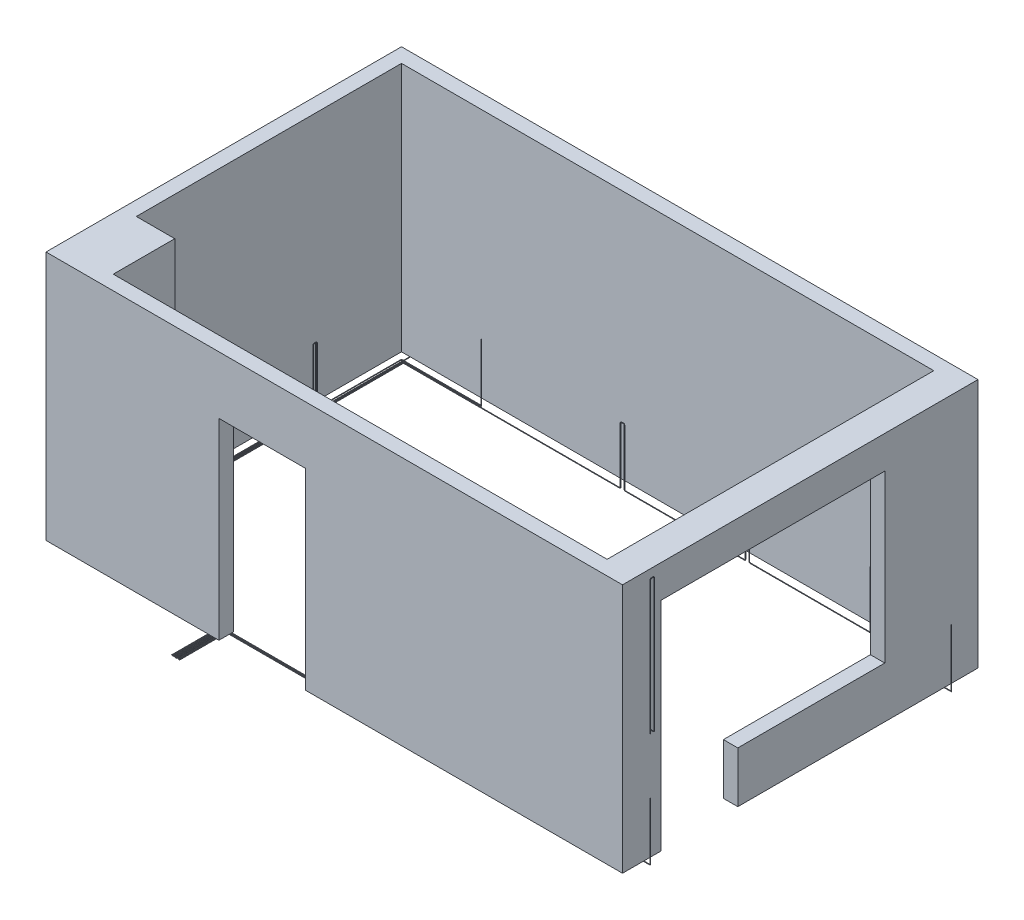
SolidWorks part; units mm, degrees
ref_plane "Front Plane" through (0, 0, 0) normal (0, 0, 1) x (1, 0, 0)
ref_plane "Top Plane" through (0, 0, 0) normal (0, 1, 0) x (1, 0, 0)
ref_plane "Right Plane" through (0, 0, 0) normal (1, 0, 0) x (0, 0, -1)
sketch "LR Dimensions" plane through (0, 0, 0) normal (0, 1, 0) x (1, 0, 0)
  line L0 (-275.7723, 265.5066) -> (-275.7723, -104.4934)
  line L1 (-260.7723, 250.5066) -> (309.2277, 250.5066)
  line L2 (-260.7723, 250.5066) -> (-260.7723, -89.4934)
  line L7 (-275.7723, 265.5066) -> (324.2277, 265.5066)
  line L8 (-260.7723, -89.4934) -> (309.2277, -89.4934) construction
  line L9 (-275.7723, -104.4934) -> (324.2277, -104.4934) construction
  line L10 (-260.7723, -89.4934) -> (-120.7723, -89.4934)
  line L11 (-275.7723, -104.4934) -> (-120.7723, -104.4934)
  line L12 (309.2277, -89.4934) -> (-30.7723, -89.4934)
  line L13 (324.2277, -104.4934) -> (-30.7723, -104.4934)
  line L14 (309.2277, -89.4934) -> (309.2277, -49.4934)
  line L15 (309.2277, 250.5066) -> (309.2277, -89.4934) construction
  line L16 (324.2277, 265.5066) -> (324.2277, -104.4934) construction
  line L17 (324.2277, -104.4934) -> (324.2277, -49.4934)
  line L18 (324.2277, 265.5066) -> (324.2277, 30.5066)
  line L19 (309.2277, 250.5066) -> (309.2277, 30.5066)
  line L20 (309.2277, 30.5066) -> (324.2277, 30.5066)
  line L21 (309.2277, -49.4934) -> (324.2277, -49.4934)
  line L22 (-30.7723, -89.4934) -> (-30.7723, -104.4934)
  line L23 (-120.7723, -104.4934) -> (-120.7723, -89.4934)
  line L24 (-260.7723, -25.4934) -> (-220.7723, -25.4934)
  line L25 (-220.7723, -25.4934) -> (-220.7723, -89.4934)
  line L26 (-30.7723, -89.4934) -> (-120.7723, -89.4934)
  line L27 (-120.7723, -104.4934) -> (-30.7723, -104.4934)
  line L28 (324.2277, -49.4934) -> (324.2277, 30.5066)
  line L29 (309.2277, 30.5066) -> (309.2277, -49.4934)
  point P8 (316.7277, -49.4934)
  dimension "D1" = 90
  dimension "D2" = 140
  dimension "D4" = 80
  dimension "D5" = 40
  dimension "D6" = 64
  dimension "D7" = 40
  dimension "D8" = 570
  dimension "D9" = 340
  dimension "D3" = 15
extrude "LR Walls Extrude" add sketch "LR Dimensions" along normal blind 260 contours L23 L27 L22 L26 | L12 L22 L13 L17 L21 L14 | L20 L29 L21 L28 | L11 L23 L10 L2 L1 L19 L20 L18 L7 L0 | L25 L24 L2 L10
sketch "LR Balcony Hole Dimensions" plane through (324.2277, 0, 0) normal (1, 0, 0) x (0, 0, -1)
  line L0 (-104.4934, 0) -> (265.5066, 0) construction
  line L2 (-64.4934, 226) -> (-64.4934, 0)
  line L3 (-64.4934, 0) -> (15.5066, 0)
  line L6 (15.5066, 53) -> (168.5066, 53)
  line L10 (15.5066, 53) -> (15.5066, 0)
  line L11 (-104.4934, 260) -> (-104.4934, 0) construction
  line L12 (-64.4934, 226) -> (168.5066, 226)
  line L13 (168.5066, 226) -> (168.5066, 53)
  line L14 (-104.4934, 260) -> (265.5066, 260) construction
  line L15 (265.5066, 260) -> (265.5066, 0) construction
  dimension "D1" = 40
  dimension "D2" = 80
  dimension "D3" = 53
  dimension "D4" = 34
  dimension "D5" = 97
extrude "LR Balcony Hole Cut" cut sketch "LR Balcony Hole Dimensions" against normal blind 15
sketch "LR Support" plane through (0, 0, 89.4934) normal (0, 0, -1) x (-1, 0, 0)
  line L1 (-309.2277, 260) -> (-293.2277, 260)
  line L2 (-309.2277, 260) -> (-309.2277, 230)
  line L3 (-309.2277, 230) -> (-293.2277, 230)
  line L4 (-293.2277, 260) -> (-293.2277, 230)
  dimension "D1" = 30
  dimension "D2" = 16
extrude "LR Support Extrude" add sketch "LR Support" along normal up to surface (340 mm away) up to face at (24.2277, 130, -250.5066)
sketch "LR Door Dimensions" plane through (0, 0, 104.4934) normal (0, 0, 1) x (1, 0, 0)
  line L0 (-275.7723, 0) -> (324.2277, 0) construction
  line L1 (-95.7723, 0) -> (-5.7723, 0)
  line L2 (-95.7723, 0) -> (-95.7723, 200)
  line L3 (-95.7723, 200) -> (-5.7723, 200)
  line L4 (-5.7723, 0) -> (-5.7723, 200)
  line L5 (-275.7723, 260) -> (-275.7723, 0) construction
  dimension "D1" = 90
  dimension "D2" = 180
  dimension "D3" = 200
extrude "LR Door Hole Cut" cut sketch "LR Door Dimensions" against normal blind 15
ref_plane "Cable Plane" through (0, -5, 0) normal (0, 1, 0) x (1, 0, 0)
sketch "Joined El lines sketch" plane through (0, -5, 0) normal (0, 1, 0) x (1, 0, 0)
  line L0 (-110.7723, 0) -> (-110.7723, -33.3999) construction
  line L1 (-258.7723, -23.4934) -> (-258.7723, 64.5066)
  line L2 (-258.7723, -23.4934) -> (-218.7723, -23.4934)
  line L3 (-218.7723, -23.4934) -> (-218.7723, -87.4934)
  line L4 (-218.7723, -87.4934) -> (-154.7723, -87.4934)
  line L5 (-258.7723, 156.5066) -> (-258.7723, 68.5066)
  line L6 (-260.7723, 250.5066) -> (-260.7723, -25.4934) construction
  line L7 (-260.7723, -25.4934) -> (-220.7723, -25.4934) construction
  line L8 (-220.7723, -25.4934) -> (-220.7723, -89.4934) construction
  line L9 (-258.7723, 160.5066) -> (-258.7723, 248.5066)
  line L10 (-80.7723, 53.0463) -> (-80.7723, -65.5533) construction
  line L11 (-100.7723, 11.838) -> (-100.7723, -42.9389) construction
  line L12 (-150.7723, -87.4934) -> (-110.7723, -87.4934)
  line L13 (-258.7723, 248.5066) -> (-175.7723, 248.5066)
  line L14 (-260.7723, 250.5066) -> (293.2277, 250.5066) construction
  line L15 (-110.7723, -87.4934) -> (-110.7723, -137.4934)
  line L16 (-258.7723, 68.5066) -> (-258.7723, 64.5066)
  line L17 (-258.7723, 160.5066) -> (-258.7723, 156.5066)
  line L18 (-154.7723, -87.4934) -> (-150.7723, -87.4934)
  line L19 (-108.7723, -137.4934) -> (-108.7723, -85.4934)
  line L20 (-108.7723, -85.4934) -> (-216.7723, -85.4934)
  line L21 (-216.7723, -85.4934) -> (-216.7723, -21.4934)
  line L22 (-216.7723, -21.4934) -> (-256.7723, -21.4934)
  line L23 (-256.7723, -21.4934) -> (-256.7723, 293.9035)
  line L24 (-106.7723, -137.4934) -> (-106.7723, -83.4934)
  line L25 (-106.7723, -83.4934) -> (-214.7723, -83.4934)
  line L26 (-214.7723, -83.4934) -> (-214.7723, -19.4934)
  line L27 (-214.7723, -19.4934) -> (-254.7723, -19.4934)
  line L28 (-254.7723, -19.4934) -> (-254.7723, 246.5066)
  line L29 (-254.7723, 246.5066) -> (-28.7723, 246.5066)
  line L30 (293.2277, -89.4934) -> (-220.7723, -89.4934) construction
  line L31 (-104.7723, -137.4934) -> (-104.7723, -87.4934)
  line L32 (-104.7723, -87.4934) -> (124.2277, -87.4934)
  line L33 (9.2277, 53.0463) -> (9.2277, -65.5533) construction
  line L34 (124.2277, -87.4934) -> (128.2277, -87.4934)
  line L35 (128.2277, -87.4934) -> (307.2277, -87.4934)
  line L36 (-26.7723, 222.0169) -> (-26.7723, 156.5066) construction
  line L37 (103.2277, 222.0169) -> (103.2277, 156.5066) construction
  line L38 (233.2277, 222.0169) -> (233.2277, 160.5066) construction
  line L39 (293.2277, 250.5066) -> (293.2277, -89.4934) construction
  line L40 (-171.7723, 222.0169) -> (-171.7723, 156.5066) construction
  line L41 (-28.7723, 246.5066) -> (-24.7723, 246.5066)
  line L42 (-24.7723, 246.5066) -> (101.2277, 246.5066)
  line L43 (101.2277, 246.5066) -> (105.2277, 246.5066)
  line L44 (105.2277, 246.5066) -> (231.2277, 246.5066)
  line L45 (231.2277, 246.5066) -> (235.2277, 246.5066)
  line L46 (235.2277, 246.5066) -> (307.2277, 246.5066)
  line L47 (324.2277, -104.4934) -> (324.2277, 265.5066) construction
  line L48 (307.2277, -87.4934) -> (307.2277, -77.4934)
  line L49 (307.2277, -77.4934) -> (326.2277, -77.4934)
  line L50 (307.2277, 246.5066) -> (307.2277, 235.5066)
  line L51 (307.2277, 235.5066) -> (326.2277, 235.5066)
  line L52 (309.2277, -89.4934) -> (309.2277, -64.4934) construction
  line L53 (309.2277, 250.5066) -> (309.2277, -89.4934) construction
  dimension "D1" = 10
  dimension "D2" = 2
  dimension "D3" = 2
  dimension "D4" = 2
  dimension "D5" = 4
  dimension "D6" = 140
  dimension "D7" = 20
  dimension "D8" = 4
  dimension "D9" = 2
  dimension "D10" = 90
  dimension "D11" = 90
  dimension "D12" = 4
  dimension "D13" = 4
  dimension "D14" = 2
  dimension "D15" = 2
  dimension "D16" = 85
  dimension "D17" = 4
  dimension "D18" = 4
  dimension "D19" = 2
  dimension "D20" = 4
  dimension "D21" = 6
  dimension "D22" = 2
  dimension "D23" = 6
  dimension "D24" = 6
  dimension "D25" = 6
  dimension "D26" = 2
  dimension "D27" = 40
  dimension "D28" = 2
  dimension "D29" = 115
  dimension "D30" = 90
  dimension "D31" = 4
  dimension "D32" = 2
  dimension "D33" = 60
  dimension "D34" = 130
  dimension "D35" = 130
  dimension "D36" = 4
  dimension "D37" = 145
  dimension "D38" = 2
  dimension "D39" = 2
  dimension "D40" = 4
  dimension "D41" = 4
  dimension "D42" = 4
  dimension "D43" = 4
  dimension "D44" = 2
  dimension "D45" = 2
  dimension "D46" = 2
  dimension "D47" = 2
  dimension "D48" = 12
  dimension "D49" = 2
  dimension "D50" = 15
sketch3d "El line 1 scetch"
  line L0 (-111.7723, -5, 87.4934) -> (-149.7723, -5, 87.4934)
  line L1 (-155.7723, -5, 87.4934) -> (-217.7723, -5, 87.4934)
  line L2 (-218.7723, -5, 86.4934) -> (-218.7723, -5, 24.4934)
  line L3 (-219.7723, -5, 23.4934) -> (-257.7723, -5, 23.4934)
  line L4 (-258.7723, -5, 22.4934) -> (-258.7723, -5, -63.5066)
  line L5 (-258.7723, -5, -69.5066) -> (-258.7723, -5, -155.5066)
  line L6 (-258.7723, -5, -161.5066) -> (-258.7723, -5, -247.5066)
  line L7 (-257.7723, -5, -248.5066) -> (-176.7723, -5, -248.5066)
  line L8 (-258.7723, -4, -64.5066) -> (-258.7723, 54, -64.5066)
  line L9 (-258.7723, -4, -68.5066) -> (-258.7723, 54, -68.5066)
  line L10 (-258.7723, -4, -156.5066) -> (-258.7723, 54, -156.5066)
  line L11 (-258.7723, -4, -160.5066) -> (-258.7723, 54, -160.5066)
  line L12 (-175.7723, -4, -248.5066) -> (-175.7723, 55, -248.5066)
  line L13 (-150.7723, -4, 87.4934) -> (-150.7723, 54, 87.4934)
  line L14 (-154.7723, -4, 87.4934) -> (-154.7723, 54, 87.4934)
  line L15 (-153.7723, 55, 87.4934) -> (-151.7723, 55, 87.4934)
  line L16 (-258.7723, 55, -67.5066) -> (-258.7723, 55, -65.5066)
  line L17 (-258.7723, 55, -157.5066) -> (-258.7723, 55, -159.5066)
  line L18 (-110.7723, -5, 88.4934) -> (-110.7723, -5, 137.4934)
  arc A0 (-175.7723, -4, -248.5066) -> (-176.7723, -5, -248.5066) centre (-176.7723, -4, -248.5066) ccw
  arc A1 (-257.7723, -5, -248.5066) -> (-258.7723, -5, -247.5066) centre (-257.7723, -5, -247.5066) ccw
  arc A2 (-258.7723, 54, -156.5066) -> (-258.7723, 55, -157.5066) centre (-258.7723, 54, -157.5066) ccw
  arc A3 (-258.7723, 54, -160.5066) -> (-258.7723, 55, -159.5066) centre (-258.7723, 54, -159.5066) ccw
  arc A4 (-258.7723, -5, -161.5066) -> (-258.7723, -4, -160.5066) centre (-258.7723, -4, -161.5066) ccw
  arc A5 (-258.7723, -4, -156.5066) -> (-258.7723, -5, -155.5066) centre (-258.7723, -4, -155.5066) ccw
  arc A6 (-258.7723, -5, -69.5066) -> (-258.7723, -4, -68.5066) centre (-258.7723, -4, -69.5066) ccw
  arc A7 (-258.7723, 54, -68.5066) -> (-258.7723, 55, -67.5066) centre (-258.7723, 54, -67.5066) ccw
  arc A8 (-258.7723, 54, -64.5066) -> (-258.7723, 55, -65.5066) centre (-258.7723, 54, -65.5066) ccw
  arc A9 (-258.7723, -4, -64.5066) -> (-258.7723, -5, -63.5066) centre (-258.7723, -4, -63.5066) ccw
  arc A10 (-258.7723, -5, 22.4934) -> (-257.7723, -5, 23.4934) centre (-257.7723, -5, 22.4934) ccw
  arc A11 (-219.7723, -5, 23.4934) -> (-218.7723, -5, 24.4934) centre (-219.7723, -5, 24.4934) ccw
  arc A12 (-218.7723, -5, 86.4934) -> (-217.7723, -5, 87.4934) centre (-217.7723, -5, 86.4934) ccw
  arc A13 (-155.7723, -5, 87.4934) -> (-154.7723, -4, 87.4934) centre (-155.7723, -4, 87.4934) ccw
  arc A14 (-154.7723, 54, 87.4934) -> (-153.7723, 55, 87.4934) centre (-153.7723, 54, 87.4934) ccw
  arc A15 (-150.7723, 54, 87.4934) -> (-151.7723, 55, 87.4934) centre (-151.7723, 54, 87.4934) ccw
  arc A16 (-150.7723, -4, 87.4934) -> (-149.7723, -5, 87.4934) centre (-149.7723, -4, 87.4934) ccw
  arc A17 (-110.7723, -5, 88.4934) -> (-111.7723, -5, 87.4934) centre (-111.7723, -5, 88.4934) ccw
  point P33 (-175.7723, -5, -248.5066)
  point P34 (-176.7723, -4, -249.5066)
  point P37 (-258.7723, -5, -248.5066)
  point P38 (-257.7723, -4, -247.5066)
  point P41 (-258.7723, 55, -156.5066)
  point P42 (-259.7723, 54, -157.5066)
  point P45 (-258.7723, 55, -160.5066)
  point P46 (-257.7723, 54, -159.5066)
  point P49 (-258.7723, -5, -160.5066)
  point P50 (-259.7723, -4, -161.5066)
  point P53 (-258.7723, -5, -156.5066)
  point P54 (-259.7723, -4, -155.5066)
  point P57 (-258.7723, -5, -68.5066)
  point P58 (-259.7723, -4, -69.5066)
  point P61 (-258.7723, 55, -68.5066)
  point P62 (-257.7723, 54, -67.5066)
  point P65 (-258.7723, 55, -64.5066)
  point P66 (-259.7723, 54, -65.5066)
  point P69 (-258.7723, -5, -64.5066)
  point P70 (-259.7723, -4, -63.5066)
  point P73 (-258.7723, -5, 23.4934)
  point P74 (-257.7723, -4, 22.4934)
  point P77 (-218.7723, -5, 23.4934)
  point P78 (-219.7723, -6, 24.4934)
  point P81 (-218.7723, -5, 87.4934)
  point P82 (-217.7723, -4, 86.4934)
  point P85 (-154.7723, -5, 87.4934)
  point P86 (-155.7723, -4, 88.4934)
  point P89 (-154.7723, 55, 87.4934)
  point P90 (-153.7723, 54, 86.4934)
  point P93 (-150.7723, 55, 87.4934)
  point P94 (-151.7723, 54, 88.4934)
  point P97 (-150.7723, -5, 87.4934)
  point P98 (-149.7723, -4, 88.4934)
  point P102 (-110.7723, -5, 87.4934)
  point P103 (-111.7723, -4, 88.4934)
  dimension "D6" = 1
  dimension "D7" = 1
  dimension "D1" = 90
  dimension "D2" = 60
  dimension "D3" = 60
  dimension "D4" = 60
  dimension "D5" = 60
sweep "El line 1" add path "El line 1 scetch" circular profile diameter 0.5 parameters "D3"=0.5
sketch3d "El line 2 sketch"
  line L0 (-256.7723, -5, -293.9035) -> (-256.7723, -5, 20.4934)
  line L1 (-255.7723, -5, 21.4934) -> (-217.7723, -5, 21.4934)
  line L2 (-216.7723, -5, 22.4934) -> (-216.7723, -5, 84.4934)
  line L3 (-215.7723, -5, 85.4934) -> (-109.7723, -5, 85.4934)
  line L4 (-108.7723, -5, 86.4934) -> (-108.7723, -5, 137.4934)
  arc A0 (-255.7723, -5, 21.4934) -> (-256.7723, -5, 20.4934) centre (-255.7723, -5, 20.4934) ccw
  arc A1 (-216.7723, -5, 22.4934) -> (-217.7723, -5, 21.4934) centre (-217.7723, -5, 22.4934) ccw
  arc A2 (-215.7723, -5, 85.4934) -> (-216.7723, -5, 84.4934) centre (-215.7723, -5, 84.4934) ccw
  arc A3 (-109.7723, -5, 85.4934) -> (-108.7723, -5, 86.4934) centre (-109.7723, -5, 86.4934) ccw
  point P14 (-256.7723, -5, 21.4934)
  point P15 (-255.7723, -6, 20.4934)
  point P18 (-216.7723, -5, 21.4934)
  point P19 (-217.7723, -4, 22.4934)
  point P22 (-216.7723, -5, 85.4934)
  point P23 (-215.7723, -6, 84.4934)
  point P26 (-108.7723, -5, 85.4934)
  point P27 (-109.7723, -6, 86.4934)
  dimension "D1" = 1
sweep "El line 2" add path "El line 2 sketch" circular profile diameter 0.5 parameters "D3"=0.5
sketch3d "El line 3 sketch"
  line L0 (-28.7723, -4, -246.5066) -> (-28.7723, 54, -246.5066)
  line L1 (-24.7723, -4, -246.5066) -> (-24.7723, 54, -246.5066)
  line L2 (101.2277, -4, -246.5066) -> (101.2277, 54, -246.5066)
  line L3 (236.2277, -5, -246.5066) -> (306.2277, -5, -246.5066)
  line L4 (230.2277, -5, -246.5066) -> (106.2277, -5, -246.5066)
  line L5 (100.2277, -5, -246.5066) -> (-23.7723, -5, -246.5066)
  line L6 (-29.7723, -5, -246.5066) -> (-253.7723, -5, -246.5066)
  line L7 (-254.7723, -5, -245.5066) -> (-254.7723, -5, 18.4934)
  line L8 (-253.7723, -5, 19.4934) -> (-215.7723, -5, 19.4934)
  line L9 (-214.7723, -5, 20.4934) -> (-214.7723, -5, 82.4934)
  line L10 (-213.7723, -5, 83.4934) -> (-107.7723, -5, 83.4934)
  line L11 (-106.7723, -5, 84.4934) -> (-106.7723, -5, 137.4934)
  line L12 (105.2277, -4, -246.5066) -> (105.2277, 54, -246.5066)
  line L13 (231.2277, -4, -246.5066) -> (231.2277, 54, -246.5066)
  line L14 (235.2277, -4, -246.5066) -> (235.2277, 54, -246.5066)
  line L15 (-27.7723, 55, -246.5066) -> (-25.7723, 55, -246.5066)
  line L16 (104.2277, 55, -246.5066) -> (102.2277, 55, -246.5066)
  line L18 (234.2277, 55, -246.5066) -> (232.2277, 55, -246.5066)
  line L19 (307.2277, -5, -245.5066) -> (307.2277, -5, -236.5066)
  line L20 (308.2277, -5, -235.5066) -> (326.2277, -5, -235.5066)
  line L22 (326.2277, -5, -235.5066) -> (326.2277, 55, -235.5066)
  arc A0 (234.2277, 55, -246.5066) -> (235.2277, 54, -246.5066) centre (234.2277, 54, -246.5066) ccw
  arc A1 (231.2277, 54, -246.5066) -> (232.2277, 55, -246.5066) centre (232.2277, 54, -246.5066) ccw
  arc A2 (230.2277, -5, -246.5066) -> (231.2277, -4, -246.5066) centre (230.2277, -4, -246.5066) ccw
  arc A3 (235.2277, -4, -246.5066) -> (236.2277, -5, -246.5066) centre (236.2277, -4, -246.5066) ccw
  arc A4 (308.2277, -5, -235.5066) -> (307.2277, -5, -236.5066) centre (308.2277, -5, -236.5066) ccw
  arc A5 (104.2277, 55, -246.5066) -> (105.2277, 54, -246.5066) centre (104.2277, 54, -246.5066) ccw
  arc A6 (101.2277, 54, -246.5066) -> (102.2277, 55, -246.5066) centre (102.2277, 54, -246.5066) ccw
  arc A7 (106.2277, -5, -246.5066) -> (105.2277, -4, -246.5066) centre (106.2277, -4, -246.5066) ccw
  arc A8 (101.2277, -4, -246.5066) -> (100.2277, -5, -246.5066) centre (100.2277, -4, -246.5066) ccw
  arc A9 (-28.7723, 54, -246.5066) -> (-27.7723, 55, -246.5066) centre (-27.7723, 54, -246.5066) ccw
  arc A10 (-24.7723, 54, -246.5066) -> (-25.7723, 55, -246.5066) centre (-25.7723, 54, -246.5066) ccw
  arc A11 (-23.7723, -5, -246.5066) -> (-24.7723, -4, -246.5066) centre (-23.7723, -4, -246.5066) ccw
  arc A12 (-28.7723, -4, -246.5066) -> (-29.7723, -5, -246.5066) centre (-29.7723, -4, -246.5066) ccw
  arc A13 (-253.7723, -5, -246.5066) -> (-254.7723, -5, -245.5066) centre (-253.7723, -5, -245.5066) ccw
  arc A14 (-253.7723, -5, 19.4934) -> (-254.7723, -5, 18.4934) centre (-253.7723, -5, 18.4934) ccw
  arc A15 (-214.7723, -5, 20.4934) -> (-215.7723, -5, 19.4934) centre (-215.7723, -5, 20.4934) ccw
  arc A16 (-213.7723, -5, 83.4934) -> (-214.7723, -5, 82.4934) centre (-213.7723, -5, 82.4934) ccw
  arc A17 (-107.7723, -5, 83.4934) -> (-106.7723, -5, 84.4934) centre (-107.7723, -5, 84.4934) ccw
  arc A18 (307.2277, -5, -245.5066) -> (306.2277, -5, -246.5066) centre (306.2277, -5, -245.5066) ccw
  point P44 (235.2277, 55, -246.5066)
  point P46 (234.2277, 54, -247.5066)
  point P50 (231.2277, 55, -246.5066)
  point P51 (232.2277, 54, -247.5066)
  point P54 (231.2277, -5, -246.5066)
  point P55 (230.2277, -4, -245.5066)
  point P58 (235.2277, -5, -246.5066)
  point P59 (236.2277, -4, -245.5066)
  point P63 (307.2277, -5, -235.5066)
  point P66 (105.2277, 55, -246.5066)
  point P67 (104.2277, 54, -247.5066)
  point P70 (101.2277, 55, -246.5066)
  point P71 (102.2277, 54, -247.5066)
  point P74 (105.2277, -5, -246.5066)
  point P75 (106.2277, -4, -247.5066)
  point P78 (101.2277, -5, -246.5066)
  point P79 (100.2277, -4, -247.5066)
  point P82 (-28.7723, 55, -246.5066)
  point P83 (-27.7723, 54, -247.5066)
  point P86 (-24.7723, 55, -246.5066)
  point P87 (-25.7723, 54, -245.5066)
  point P90 (-24.7723, -5, -246.5066)
  point P91 (-23.7723, -4, -247.5066)
  point P94 (-28.7723, -5, -246.5066)
  point P95 (-29.7723, -4, -247.5066)
  point P98 (-254.7723, -5, -246.5066)
  point P99 (-253.7723, -4, -245.5066)
  point P102 (-254.7723, -5, 19.4934)
  point P103 (-253.7723, -6, 18.4934)
  point P106 (-214.7723, -5, 19.4934)
  point P107 (-215.7723, -4, 20.4934)
  point P110 (-214.7723, -5, 83.4934)
  point P111 (-213.7723, -6, 82.4934)
  point P114 (-106.7723, -5, 83.4934)
  point P115 (-107.7723, -6, 84.4934)
  point P119 (308.2277, -6, -236.5066)
  point P122 (307.2277, -5, -246.5066)
  point P123 (306.2277, -4, -245.5066)
  dimension "D5" = 1
  dimension "D1" = 1
  dimension "D2" = 60
  dimension "D6" = 60
  dimension "D3" = 60
  dimension "D4" = 60
sweep "El line 3" add path "El line 3 sketch" circular profile diameter 0.5 parameters "D3"=0.5
sketch3d "El line 4 sketch"
  line L0 (-104.7723, -5, 137.4934) -> (-104.7723, -5, 88.4934)
  line L1 (-103.7723, -5, 87.4934) -> (123.2277, -5, 87.4934)
  line L2 (129.2277, -5, 87.4934) -> (306.2277, -5, 87.4934)
  line L3 (326.2277, -4, 77.4934) -> (326.2277, 55, 77.4934)
  line L4 (124.2277, -4, 87.4934) -> (124.2277, 54, 87.4934)
  line L5 (128.2277, -4, 87.4934) -> (128.2277, 54, 87.4934)
  line L6 (125.2277, 55, 87.4934) -> (127.2277, 55, 87.4934)
  line L7 (307.2277, -5, 86.4934) -> (307.2277, -5, 78.4934)
  line L8 (308.2277, -5, 77.4934) -> (325.2277, -5, 77.4934)
  arc A0 (326.2277, -4, 77.4934) -> (325.2277, -5, 77.4934) centre (325.2277, -4, 77.4934) ccw
  arc A1 (129.2277, -5, 87.4934) -> (128.2277, -4, 87.4934) centre (129.2277, -4, 87.4934) ccw
  arc A2 (128.2277, 54, 87.4934) -> (127.2277, 55, 87.4934) centre (127.2277, 54, 87.4934) ccw
  arc A3 (125.2277, 55, 87.4934) -> (124.2277, 54, 87.4934) centre (125.2277, 54, 87.4934) ccw
  arc A4 (124.2277, -4, 87.4934) -> (123.2277, -5, 87.4934) centre (123.2277, -4, 87.4934) ccw
  arc A5 (-103.7723, -5, 87.4934) -> (-104.7723, -5, 88.4934) centre (-103.7723, -5, 88.4934) ccw
  arc A6 (308.2277, -5, 77.4934) -> (307.2277, -5, 78.4934) centre (308.2277, -5, 78.4934) ccw
  arc A7 (306.2277, -5, 87.4934) -> (307.2277, -5, 86.4934) centre (306.2277, -5, 86.4934) ccw
  point P16 (326.2277, -5, 77.4934)
  point P17 (325.2277, -4, 76.4934)
  point P20 (128.2277, -5, 87.4934)
  point P21 (129.2277, -4, 86.4934)
  point P24 (128.2277, 55, 87.4934)
  point P25 (127.2277, 54, 88.4934)
  point P28 (124.2277, 55, 87.4934)
  point P29 (125.2277, 54, 88.4934)
  point P32 (124.2277, -5, 87.4934)
  point P33 (123.2277, -4, 86.4934)
  point P36 (-104.7723, -5, 87.4934)
  point P37 (-103.7723, -4, 88.4934)
  point P44 (307.2277, -5, 77.4934)
  point P45 (308.2277, -4, 78.4934)
  point P48 (307.2277, -5, 87.4934)
  point P49 (306.2277, -4, 86.4934)
  dimension "D3" = 1
  dimension "D1" = 60
  dimension "D2" = 60
sweep "El line 4" add path "El line 4 sketch" circular profile diameter 0.5 parameters "D3"=0.5
sketch3d "Net lines 1 & 2 sketch"
  line L0 (-111.7519, -4.7987, 137.4729) -> (-111.7519, -4.7987, 89.4729)
  line L1 (-112.7519, -4.7987, 88.4729) -> (-218.7519, -4.7987, 88.4729)
  line L2 (-219.7519, -4.7987, 87.4729) -> (-219.7519, -4.7987, 25.4729)
  line L3 (-220.7519, -4.7987, 24.4729) -> (-258.7519, -4.7987, 24.4729)
  line L4 (-259.7519, -4.7987, 23.4729) -> (-259.7519, -4.7987, -65.5271)
  line L5 (-258.7723, -5, 23.4934) -> (-258.7723, -5, -64.5066) construction
  line L7 (-258.7723, -5, 23.4934) -> (-218.7723, -5, 23.4934) construction
  line L8 (-218.7723, -5, 23.4934) -> (-218.7723, -5, 87.4934) construction
  line L9 (-218.7723, -5, 87.4934) -> (-154.7723, -5, 87.4934) construction
  line L10 (-110.7723, -5, 87.4934) -> (-110.7723, -5, 137.4934) construction
  line L11 (-259.7519, -3.7987, -66.5271) -> (-259.7519, 55.2013, -66.5271)
  arc A0 (-111.7519, -4.7987, 89.4729) -> (-112.7519, -4.7987, 88.4729) centre (-112.7519, -4.7987, 89.4729) ccw
  arc A1 (-218.7519, -4.7987, 88.4729) -> (-219.7519, -4.7987, 87.4729) centre (-218.7519, -4.7987, 87.4729) ccw
  arc A2 (-219.7519, -4.7987, 25.4729) -> (-220.7519, -4.7987, 24.4729) centre (-220.7519, -4.7987, 25.4729) ccw
  arc A3 (-258.7519, -4.7987, 24.4729) -> (-259.7519, -4.7987, 23.4729) centre (-258.7519, -4.7987, 23.4729) ccw
  arc A4 (-259.7519, -3.7987, -66.5271) -> (-259.7519, -4.7987, -65.5271) centre (-259.7519, -3.7987, -65.5271) ccw
  point P19 (-111.7519, -4.7987, 88.4729)
  point P20 (-112.7519, -3.7987, 89.4729)
  point P23 (-219.7519, -4.7987, 88.4729)
  point P24 (-218.7519, -5.7987, 87.4729)
  point P27 (-219.7519, -4.7987, 24.4729)
  point P28 (-220.7519, -3.7987, 25.4729)
  point P31 (-259.7519, -4.7987, 24.4729)
  point P32 (-258.7519, -5.7987, 23.4729)
  point P35 (-259.7519, -4.7987, -66.5271)
  point P36 (-260.7519, -3.7987, -65.5271)
  dimension "D8" = 1
  dimension "D9" = 1
  dimension "D1" = 1
  dimension "D7" = 91
  dimension "D2" = 1
  dimension "D3" = 1
  dimension "D4" = 1
  dimension "D5" = 1
  dimension "D6" = 49
  dimension "D10" = 60
sweep "Net lines 1 & 2" add path "Net lines 1 & 2 sketch" circular profile diameter 0.5 parameters "D3"=0.5
sketch3d "Net lines 3 & 4 sketch"
  line L0 (-109.7723, -5, 137.4934) -> (-109.7723, -5, 87.4934)
  line L1 (-110.7723, -5, 86.4934) -> (-216.7723, -5, 86.4934)
  line L2 (-217.7723, -5, 85.4934) -> (-217.7723, -5, 23.4934)
  line L3 (-218.7723, -5, 22.4934) -> (-256.7723, -5, 22.4934)
  line L4 (-257.7723, -5, 21.4934) -> (-257.7723, -5, -157.5066)
  line L5 (-108.7723, -5, 137.4934) -> (-108.7723, -5, 85.4934) construction
  line L6 (-108.7723, -5, 85.4934) -> (-216.7723, -5, 85.4934) construction
  line L7 (-216.7723, -5, 85.4934) -> (-216.7723, -5, 21.4934) construction
  line L8 (-216.7723, -5, 21.4934) -> (-256.7723, -5, 21.4934) construction
  line L9 (-256.7723, -5, 21.4934) -> (-256.7723, -5, -293.9035) construction
  line L12 (-257.7723, -4, -158.5066) -> (-257.7723, 55, -158.5066)
  arc A0 (-109.7723, -5, 87.4934) -> (-110.7723, -5, 86.4934) centre (-110.7723, -5, 87.4934) ccw
  arc A1 (-216.7723, -5, 86.4934) -> (-217.7723, -5, 85.4934) centre (-216.7723, -5, 85.4934) ccw
  arc A2 (-217.7723, -5, 23.4934) -> (-218.7723, -5, 22.4934) centre (-218.7723, -5, 23.4934) ccw
  arc A3 (-256.7723, -5, 22.4934) -> (-257.7723, -5, 21.4934) centre (-256.7723, -5, 21.4934) ccw
  arc A4 (-257.7723, -5, -157.5066) -> (-257.7723, -4, -158.5066) centre (-257.7723, -4, -157.5066) ccw
  point P18 (-109.7723, -5, 86.4934)
  point P19 (-110.7723, -4, 87.4934)
  point P22 (-217.7723, -5, 86.4934)
  point P23 (-216.7723, -6, 85.4934)
  point P26 (-217.7723, -5, 22.4934)
  point P27 (-218.7723, -4, 23.4934)
  point P30 (-257.7723, -5, 22.4934)
  point P31 (-256.7723, -6, 21.4934)
  point P35 (-257.7723, -5, -158.5066)
  point P36 (-256.7723, -4, -157.5066)
  dimension "D7" = 1
  dimension "D10" = 1
  dimension "D1" = 1
  dimension "D2" = 1
  dimension "D3" = 1
  dimension "D4" = 1
  dimension "D5" = 1
  dimension "D6" = 181
  dimension "D8" = 51
  dimension "D9" = 60
sweep "Net lines 3 & 4" add path "Net lines 3 & 4 sketch" circular profile diameter 0.5 parameters "D3"=0.5
sketch3d "Net lines 5 & 6 sketch"
  line L0 (-107.7723, -5, 137.4934) -> (-107.7723, -5, 85.4934)
  line L1 (-108.7723, -5, 84.4934) -> (-214.7723, -5, 84.4934)
  line L2 (-215.7723, -5, 83.4934) -> (-215.7723, -5, 21.4934)
  line L3 (-216.7723, -5, 20.4934) -> (-254.7723, -5, 20.4934)
  line L4 (-255.7723, -5, 19.4934) -> (-255.7723, -5, -246.5066)
  line L5 (-254.7723, -5, -247.5066) -> (-175.7723, -5, -247.5066)
  line L6 (-106.7723, -5, 137.4934) -> (-106.7723, -5, 83.4934) construction
  line L7 (-106.7723, -5, 83.4934) -> (-214.7723, -5, 83.4934) construction
  line L8 (-214.7723, -5, 83.4934) -> (-214.7723, -5, 19.4934) construction
  line L9 (-214.7723, -5, 19.4934) -> (-254.7723, -5, 19.4934) construction
  line L10 (-254.7723, -5, 19.4934) -> (-254.7723, -5, -246.5066) construction
  line L11 (-258.7723, -5, -248.5066) -> (-175.7723, -5, -248.5066) construction
  line L12 (-174.7723, -4, -247.5066) -> (-174.7723, 55, -247.5066)
  arc A0 (-107.7723, -5, 85.4934) -> (-108.7723, -5, 84.4934) centre (-108.7723, -5, 85.4934) ccw
  arc A1 (-214.7723, -5, 84.4934) -> (-215.7723, -5, 83.4934) centre (-214.7723, -5, 83.4934) ccw
  arc A2 (-215.7723, -5, 21.4934) -> (-216.7723, -5, 20.4934) centre (-216.7723, -5, 21.4934) ccw
  arc A3 (-254.7723, -5, 20.4934) -> (-255.7723, -5, 19.4934) centre (-254.7723, -5, 19.4934) ccw
  arc A4 (-255.7723, -5, -246.5066) -> (-254.7723, -5, -247.5066) centre (-254.7723, -5, -246.5066) ccw
  arc A5 (-175.7723, -5, -247.5066) -> (-174.7723, -4, -247.5066) centre (-175.7723, -4, -247.5066) ccw
  point P22 (-107.7723, -5, 84.4934)
  point P23 (-108.7723, -4, 85.4934)
  point P26 (-215.7723, -5, 84.4934)
  point P27 (-214.7723, -6, 83.4934)
  point P30 (-215.7723, -5, 20.4934)
  point P31 (-216.7723, -4, 21.4934)
  point P34 (-255.7723, -5, 20.4934)
  point P35 (-254.7723, -6, 19.4934)
  point P38 (-255.7723, -5, -247.5066)
  point P39 (-254.7723, -6, -246.5066)
  point P42 (-174.7723, -5, -247.5066)
  point P43 (-175.7723, -4, -246.5066)
  dimension "D10" = 1
  dimension "D1" = 1
  dimension "D2" = 53
  dimension "D3" = 1
  dimension "D4" = 1
  dimension "D5" = 1
  dimension "D6" = 1
  dimension "D7" = 1
  dimension "D8" = 81
  dimension "D9" = 60
sweep "Net lines 5 & 6" add path "Net lines 5 & 6 sketch" circular profile diameter 0.5 parameters "D3"=0.5
sketch3d "Net lines 7 & 8 sketch"
  line L0 (-105.75, -4.7896, 137.5157) -> (-105.75, -4.7896, 87.5157)
  line L1 (-104.75, -4.7896, 86.5157) -> (125.629, -4.7896, 86.5157)
  line L2 (-104.7723, -5, 137.4934) -> (-104.7723, -5, 87.4934) construction
  line L4 (-104.7723, -5, 87.4934) -> (124.2277, -5, 87.4934) construction
  line L5 (126.629, -3.7896, 86.5157) -> (126.629, 55.2104, 86.5157)
  arc A0 (-105.75, -4.7896, 87.5157) -> (-104.75, -4.7896, 86.5157) centre (-104.75, -4.7896, 87.5157) ccw
  arc A1 (125.629, -4.7896, 86.5157) -> (126.629, -3.7896, 86.5157) centre (125.629, -3.7896, 86.5157) ccw
  point P7 (126.629, -4.7896, 86.5157)
  point P9 (125.629, -3.7896, 87.5157)
  point P13 (-105.75, -4.7896, 86.5157)
  point P14 (-104.75, -5.7896, 87.5157)
  dimension "D4" = 1
  dimension "D6" = 1
  dimension "D1" = 1
  dimension "D2" = 1
  dimension "D3" = 240
  dimension "D5" = 60
  dimension "D7" = 51
sweep "Net lines 7 & 8" add path "Net lines 7 & 8 sketch" circular profile diameter 0.5 parameters "D3"=0.5
sketch3d "Lights line sketch"
  line L0 (-103.7723, -5, 137.7409) -> (-103.7723, -5, 89.4934)
  line L1 (-102.7723, -5, 88.4934) -> (20.2277, -5, 88.4934)
  line L2 (9.2277, -5, -53.0463) -> (9.2277, -5, 65.5533) construction
  line L3 (26.2277, -5, 88.4934) -> (307.2277, -5, 88.4934)
  line L4 (-104.7723, -5, 137.4934) -> (-104.7723, -5, 87.4934) construction
  line L5 (-104.7723, -5, 87.4934) -> (124.2277, -5, 87.4934) construction
  line L6 (308.2277, -5, 87.4934) -> (308.2277, -5, 76.4934)
  line L8 (308.2277, -4, 75.4934) -> (308.2277, 114, 75.4934)
  line L9 (309.2277, 115, 75.4934) -> (327.2277, 115, 75.4934)
  line L11 (328.2277, 116, 75.4934) -> (328.2277, 254, 75.4934)
  line L12 (328.2277, 255, 76.4934) -> (328.2277, 255, 78.4934)
  line L18 (21.2277, -4, 88.4934) -> (21.2277, 254, 88.4934)
  line L19 (25.2277, -4, 88.4934) -> (25.2277, 254, 88.4934)
  line L20 (24.2277, 255, 88.4934) -> (22.2277, 255, 88.4934)
  line L21 (328.2277, 254, 79.4934) -> (328.2277, 115, 79.4934)
  arc A0 (307.2277, -5, 88.4934) -> (308.2277, -5, 87.4934) centre (307.2277, -5, 87.4934) ccw
  arc A1 (308.2277, -5, 76.4934) -> (308.2277, -4, 75.4934) centre (308.2277, -4, 76.4934) ccw
  arc A2 (309.2277, 115, 75.4934) -> (308.2277, 114, 75.4934) centre (309.2277, 114, 75.4934) ccw
  arc A3 (327.2277, 115, 75.4934) -> (328.2277, 116, 75.4934) centre (327.2277, 116, 75.4934) ccw
  arc A4 (25.2277, 254, 88.4934) -> (24.2277, 255, 88.4934) centre (24.2277, 254, 88.4934) ccw
  arc A5 (21.2277, 254, 88.4934) -> (22.2277, 255, 88.4934) centre (22.2277, 254, 88.4934) ccw
  arc A6 (26.2277, -5, 88.4934) -> (25.2277, -4, 88.4934) centre (26.2277, -4, 88.4934) ccw
  arc A7 (21.2277, -4, 88.4934) -> (20.2277, -5, 88.4934) centre (20.2277, -4, 88.4934) ccw
  arc A8 (-102.7723, -5, 88.4934) -> (-103.7723, -5, 89.4934) centre (-102.7723, -5, 89.4934) ccw
  arc A9 (328.2277, 254, 75.4934) -> (328.2277, 255, 76.4934) centre (328.2277, 254, 76.4934) ccw
  arc A10 (328.2277, 254, 79.4934) -> (328.2277, 255, 78.4934) centre (328.2277, 254, 78.4934) ccw
  point P17 (308.2277, -5, 88.4934)
  point P21 (307.2277, -4, 87.4934)
  point P24 (308.2277, -5, 75.4934)
  point P25 (309.2277, -4, 76.4934)
  point P28 (308.2277, 115, 75.4934)
  point P29 (309.2277, 114, 76.4934)
  point P32 (328.2277, 115, 75.4934)
  point P33 (327.2277, 116, 76.4934)
  point P36 (328.2277, 255, 75.4934)
  point P39 (25.2277, 255, 88.4934)
  point P40 (24.2277, 254, 89.4934)
  point P43 (21.2277, 255, 88.4934)
  point P44 (22.2277, 254, 87.4934)
  point P47 (25.2277, -5, 88.4934)
  point P48 (26.2277, -4, 87.4934)
  point P51 (21.2277, -5, 88.4934)
  point P52 (20.2277, -4, 87.4934)
  point P55 (-103.7723, -5, 88.4934)
  point P56 (-102.7723, -4, 89.4934)
  point P58 (329.2277, 254, 76.4934)
  point P61 (328.2277, 255, 79.4934)
  point P62 (327.2277, 254, 78.4934)
  dimension "D9" = 4
  dimension "D11" = 140
  dimension "D12" = 1
  dimension "D1" = 1
  dimension "D2" = 1
  dimension "D3" = 4
  dimension "D4" = 13
  dimension "D5" = 120
  dimension "D6" = 20
  dimension "D7" = 260
  dimension "D8" = 140
  dimension "D10" = 12
sweep "Lights line" add path "Lights line sketch" circular profile diameter 0.5 parameters "D3"=0.5
